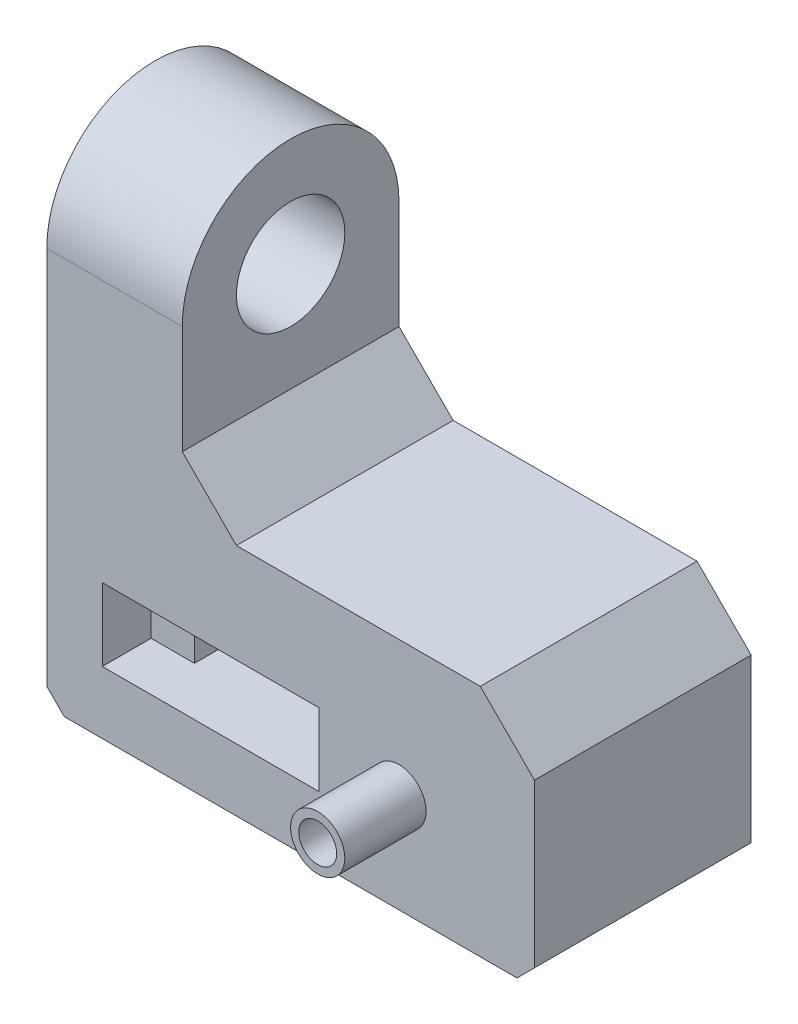
SolidWorks part; units mm, degrees
ref_plane "Front Plane" through (0, 0, 0) normal (0, 0, 1) x (1, 0, 0)
ref_plane "Top Plane" through (0, 0, 0) normal (0, 1, 0) x (1, 0, 0)
ref_plane "Right Plane" through (0, 0, 0) normal (1, 0, 0) x (0, 0, -1)
sketch "Sketch1" plane through (0, 0, 0) normal (0, 0, 1) x (1, 0, 0)
  line L1 (-90, 50) -> (0, 50)
  line L2 (-90, 50) -> (-90, 0)
  line L3 (-90, 0) -> (0, 0)
  line L4 (0, 50) -> (0, 0)
  dimension "D1" = 90
  dimension "D2" = 50
extrude "Boss-Extrude1" add sketch "Sketch1" along normal blind 40
sketch "Sketch19" plane through (0, 0, 40) normal (0, 0, 1) x (1, 0, 0)
  line L0 (-65, 25) -> (-25, 25) construction
  line L1 (-65, 25) -> (-65, 0) construction
  line L2 (-90, 0) -> (0, 0) construction
  line L3 (-65, 25) -> (-65, 50) construction
  line L4 (0, 50) -> (-90, 50) construction
  line L7 (-25, 25) -> (0, 25) construction
  line L8 (0, 0) -> (0, 50) construction
  line L9 (-65, 25) -> (-90, 25) construction
  line L10 (-90, 50) -> (-90, 0) construction
  circle A0 centre (-65, 25) radius 20
  circle A1 centre (-25, 25) radius 20
  dimension "D1" = 40
  dimension "D2" = 40
sketch "Sketch21" plane through (0, 0, 40) normal (0, 0, 1) x (1, 0, 0)
  line L1 (-30, 30) -> (-20, 30)
  line L2 (-30, 30) -> (-30, 20)
  line L3 (-30, 20) -> (-20, 20)
  line L4 (-20, 30) -> (-20, 20)
  circle A0 centre (-25, 25) radius 5
  dimension "D1" = 10
sketch "Sketch22" plane through (0, 0, 40) normal (0, 0, 1) x (1, 0, 0)
  line L0 (-79.75, 25) -> (-90, 25) construction
  line L1 (-79.75, 18.3) -> (-39.75, 18.3)
  line L2 (-79.75, 18.3) -> (-79.75, 31.7)
  line L3 (-79.75, 31.7) -> (-39.75, 31.7)
  line L4 (-39.75, 18.3) -> (-39.75, 31.7)
  line L5 (-59.75, 18.3) -> (-59.75, 0) construction
  line L6 (-90, 0) -> (0, 0) construction
  line L7 (-59.75, 31.7) -> (-59.75, 50) construction
  line L8 (0, 50) -> (-90, 50) construction
  point P16 (-59.75, 18.3)
  dimension "D1" = 10.25
  dimension "D3" = 13.4
  dimension "D4" = 40
extrude "Cut-Extrude11" cut sketch "Sketch22" against normal blind 9
sketch "Sketch24" plane through (0, 0, 31) normal (0, 0, 1) x (1, 0, 0)
  line L0 (-79.75, 18.3) -> (-39.75, 18.3) construction
  line L1 (-71.75, 18.3) -> (-47.75, 18.3)
  line L2 (-71.75, 18.3) -> (-71.75, 31.7)
  line L3 (-71.75, 31.7) -> (-47.75, 31.7)
  line L4 (-47.75, 18.3) -> (-47.75, 31.7)
  line L5 (-39.75, 31.7) -> (-79.75, 31.7) construction
  line L6 (-39.75, 25) -> (-47.75, 25) construction
  line L7 (-39.75, 18.3) -> (-39.75, 31.7) construction
  line L8 (-71.75, 25) -> (-79.75, 25) construction
  line L10 (-79.75, 31.7) -> (-79.75, 18.3) construction
  dimension "D1" = 24
extrude "Cut-Extrude12" cut sketch "Sketch24" against normal up to surface (31 mm away) up to face at (-45, 25, 0)
sketch "Sketch25" plane through (0, 0, 31) normal (0, 0, 1) x (1, 0, 0)
  line L0 (-46.25, 25) -> (-73.25, 25) construction
  circle A0 centre (-73.25, 25) radius 1.1
  circle A1 centre (-46.25, 25) radius 1.1
  dimension "D1" = 2.2
extrude "Cut-Extrude13" cut sketch "Sketch25" against normal up to surface (31 mm away) up to face at (-59.75, 25, 0)
ref_plane "Plane1" through (-45, 0, 0) normal (-1, 0, 0) x (0, 0, 1)
sketch "Sketch31" plane through (0, 50, 0) normal (0, 1, 0) x (1, 0, 0)
  line L0 (0, 0) -> (-90, 0) construction
  line L1 (-25, 0) -> (0, 0)
  line L2 (-25, 0) -> (-25, -40)
  line L3 (-25, -40) -> (0, -40)
  line L4 (0, 0) -> (0, -40)
  line L5 (-65, -40) -> (-90, -40) construction
  line L6 (-90, 0) -> (-65, 0)
  line L7 (-90, 0) -> (-90, -40)
  line L8 (-90, -40) -> (-65, -40)
  line L9 (-65, 0) -> (-65, -40)
  line M5 (0, 0) -> (-90, 0)
  line M6 (-90, 0) -> (-90, -40)
  line M7 (-90, -40) -> (0, -40)
  dimension "D1" = 25
extrude "Boss-Extrude2" add sketch "Sketch31" along normal blind 50 contours L9 M5 M6 M7
sketch "Sketch32" plane through (-65, 0, 0) normal (1, 0, 0) x (0, 0, -1)
  line L0 (0, 100) -> (-40, 100) construction
  line L1 (-40, 100) -> (-40, 50) construction
  line L2 (0, 100) -> (0, 50) construction
  circle A0 centre (-20, 80) radius 20
  circle A1 centre (-20, 80) radius 10
  line M3 (0, 50) -> (0, 100)
  line M4 (0, 100) -> (-40, 100)
  line M5 (-40, 100) -> (-40, 50)
  dimension "D1" = 20
extrude "Cut-Extrude15" cut sketch "Sketch32" against normal up to surface (25 mm away) contours A0 M4 M5 | A0 M3 M4 | A1 up to face at (-90, 50, 20)
chamfer "Chamfer1" distance 10 angle 45 4 edges at (0, 0, 20) (-90, 0, 20) (-65, 50, 20) (0, 50, 20)
sketch "Sketch35" plane through (-90, 0, 0) normal (-1, 0, 0) x (0, 0, 1)
  line L0 (22.1864, 25) -> (40, 25) construction
  line L1 (40, 5) -> (40, 45) construction
  line L2 (7.1864, 35) -> (22.1864, 35)
  line L3 (7.1864, 35) -> (7.1864, 15)
  line L4 (7.1864, 15) -> (22.1864, 15)
  line L5 (22.1864, 35) -> (22.1864, 15)
  line L6 (14.6864, 15) -> (14.6864, 10) construction
  line L7 (0, 10) -> (40, 10) construction
  dimension "D1" = 15
  dimension "D2" = 20
extrude "Cut-Extrude16" cut sketch "Sketch35" against normal up to surface (42.25 mm away) up to face at (-47.75, 25, 15.5)
sketch "Sketch36" plane through (0, 0, 40) normal (0, 0, 1) x (1, 0, 0)
  line L0 (-59, -12) -> (-71, -12)
  line L4 (-59, 0) -> (-59, -12)
  line L8 (-71, 0) -> (-71, -12)
  line L9 (-59, 0) -> (-71, 0)
  line L10 (-80, 0) -> (-10, 0) construction
  line L11 (-65, 25) -> (-65, -25.8642) construction
  line L12 (-25, 25) -> (-25, 0) construction
  line L13 (-31, 0) -> (-19, 0)
  line L14 (-31, 0) -> (-31, -12)
  line L15 (-31, -12) -> (-19, -12)
  line L16 (-19, 0) -> (-19, -12)
  line L17 (-71, -12) -> (-59, 0) construction
  line L18 (-31, 0) -> (-19, -12) construction
  line L19 (-31, -12) -> (-19, 0) construction
  circle A0 centre (-65, -6) radius 3.5
  circle A1 centre (-25, -6) radius 3.5
  point P11 (-65, 0)
  point P19 (-25, 0)
  line M11 (-80, 0) -> (-10, 0)
  dimension "D4" = 7
  dimension "D2" = 12
  dimension "D3" = 12
extrude "Boss-Extrude3" add sketch "Sketch36" against normal blind 10 contours L8 L0 L4 A0 M11 | L16 L14 L15 A1 M11
sketch "Sketch37" plane through (0, 0, 40) normal (0, 0, 1) x (1, 0, 0)
  line L1 (-93.7864, 6.7705) -> (2.2127, 6.7705)
  line L2 (-93.7864, 6.7705) -> (-93.7864, -14.3396)
  line L3 (-93.7864, -14.3396) -> (2.2127, -14.3396)
  line L4 (2.2127, 6.7705) -> (2.2127, -14.3396)
extrude "Cut-Extrude17" cut sketch "Sketch37" against normal blind 100
extrude "Boss-Extrude4" add sketch "Sketch21" along normal blind 15 contours A0
sketch "Sketch38" plane through (0, 0, 55) normal (0, 0, 1) x (1, 0, 0)
  circle A0 centre (-25, 25) radius 3.5
  dimension "D1" = 7
extrude "Cut-Extrude18" cut sketch "Sketch38" against normal blind 10
sketch "Sketch39" plane through (0, 0, 0) normal (0, 0, -1) x (-1, 0, 0)
  circle A0 centre (46.25, 25) radius 1.1
  circle A1 centre (73.25, 25) radius 1.1
extrude "Boss-Extrude5" add sketch "Sketch39" against normal up to surface (7.1864 mm away) up to face at (-74.35, 25, 7.1864)
